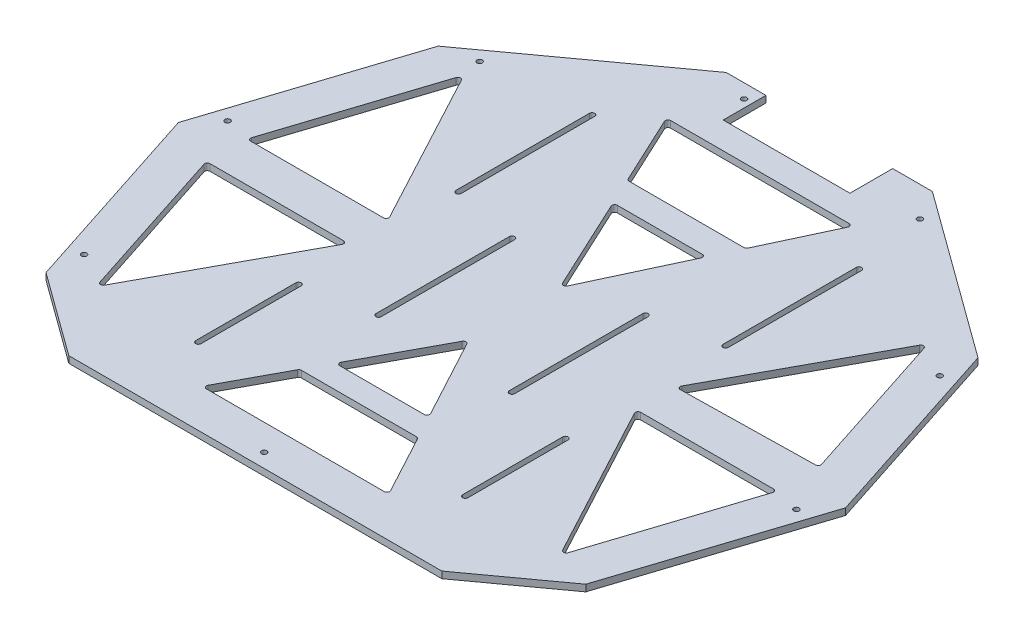
SolidWorks part; units mm, degrees
material "Alumina"
ref_plane "Front Plane" through (0, 0, 0) normal (0, 0, 1) x (1, 0, 0)
ref_plane "Top Plane" through (0, 0, 0) normal (0, 1, 0) x (1, 0, 0)
ref_plane "Right Plane" through (0, 0, 0) normal (1, 0, 0) x (0, 0, -1)
sketch "Sketch1" plane through (0, 0, 0) normal (0, 1, 0) x (1, 0, 0)
  circle A0 centre (0, 0) radius 250
extrude "Boss-Extrude1" add sketch "Sketch1" along normal blind 5
sketch "Sketch5" plane through (0, 5, 0) normal (0, 1, 0) x (1, 0, 0)
  line L0 (-139.7542, -192.3552) -> (139.7542, -192.3552)
  line L1 (202.2542, 146.9463) -> (77.2542, 237.7641)
  line L2 (77.2542, 237.7641) -> (-77.2542, 237.7641)
  line L3 (-77.2542, 237.7641) -> (-202.2542, 146.9463)
  line L4 (-202.2542, 146.9463) -> (-250, 0)
  line L5 (-250, 0) -> (-202.2542, -146.9463)
  line L7 (-202.2542, -146.9463) -> (-139.7542, -192.3552)
  line L9 (202.2542, -146.9463) -> (250, 0)
  line L10 (250, 0) -> (202.2542, 146.9463)
  line L11 (139.7542, -192.3552) -> (202.2542, -146.9463)
  line L14 (-77.2542, -237.7641) -> (77.2542, -237.7641) [skipped]
  line L15 (-202.2542, -146.9463) -> (-77.2542, -237.7641) [skipped]
  line L16 (77.2542, -237.7641) -> (202.2542, -146.9463) [skipped]
  circle A0 centre (0, 0) radius 237.7641 construction
extrude "Cut-Extrude4" cut sketch "Sketch5" against normal blind 6 flip side to cut
sketch "Sketch6" plane through (0, 0, 0) normal (0, -1, 0) x (1, 0, 0)
  circle A0 centre (-3.8992, 181.8552) radius 2
  circle A1 centre (-199.6563, 120.9633) radius 2
  circle A2 centre (-232.6258, -19.4937) radius 2
  circle A3 centre (-176.7401, -152.5047) radius 2
  circle A4 centre (-53.3458, -227.2641) radius 2
  circle A5 centre (90.4249, -215.2164) radius 2
  circle A6 centre (199.6563, -120.9633) radius 2
  circle A7 centre (232.6258, 19.4937) radius 2
extrude "Cut-Extrude5" cut sketch "Sketch6" against normal through all
sketch "Sketch7" plane through (0, 5, 0) normal (0, 1, 0) x (1, 0, 0)
  line L0 (102, 60) -> (102, 160)
  line L1 (-52, -50) -> (-52, 50)
  line L2 (-52, 50) -> (-48, 50)
  line L3 (-48, 50) -> (-48, -50)
  line L4 (-48, -50) -> (-52, -50)
  line L5 (-2, -60) -> (-2, -135)
  line L6 (48, 0) -> (48, 50)
  line L7 (48, 50) -> (52, 50)
  line L8 (52, 50) -> (52, -50)
  line L9 (52, -50) -> (48, -50)
  line L10 (48, -50) -> (48, 0)
  line L11 (98, 160) -> (98, 60)
  line L12 (-2, -135) -> (2, -135)
  line L13 (98, -60) -> (98, -135)
  line L14 (98, -135) -> (102, -135)
  line L15 (102, -60) -> (102, -135)
  line L16 (2, -60) -> (2, -135)
  line L17 (-102, -60) -> (-102, -135)
  line L18 (-102, -135) -> (-98, -135)
  line L19 (-98, -135) -> (-98, -60)
  line L20 (-102, 160) -> (-102, 60)
  line L21 (-102, 60) -> (-98, 60)
  line L22 (-98, 60) -> (-98, 160)
  line L23 (2, -135) -> (2.1286, -135.0022)
  line L24 (-2, 160) -> (-2, 60)
  line L25 (-2, 60) -> (2, 60)
  line L26 (2, 60) -> (2, 160)
  circle A0 centre (0, -60) radius 2
  circle A1 centre (100, 160) radius 2
  circle A2 centre (-50, 0) radius 2
  circle A3 centre (50, 0) radius 2
  circle A4 centre (100, 60) radius 2
  circle A5 centre (100, -60) radius 2
  circle A6 centre (100, -135) radius 2
  circle A7 centre (50, 50) radius 2
  circle A8 centre (50, -50) radius 2
  circle A9 centre (-50, -50) radius 2
  circle A10 centre (-50, 50) radius 2
  circle A11 centre (0, -135) radius 2
  circle A12 centre (-100, -60) radius 2
  circle A13 centre (-100, -135) radius 2
  circle A14 centre (-100, 60) radius 2
  circle A15 centre (-100, 160) radius 2
  circle A16 centre (0, 60) radius 2
  circle A17 centre (0, 160) radius 2
  dimension "D3" = 50
  dimension "D2" = 50
  dimension "D4" = 50
  dimension "D5" = 50
  dimension "D6" = 50
  dimension "D7" = 50
  dimension "D8" = 10
  dimension "D9" = 100
  dimension "D10" = 10
  dimension "D11" = 75
extrude "Cut-Extrude6" cut sketch "Sketch7" against normal through all contours A15 L20 A14 L22 | L21 A14 | L21 A14 | A15 | A4 | A4 L0 A1 L11 | A1 | A6 L15 A5 L13 | L14 A6 | L14 A6 | A13 L19 A12 L17 | L18 A13 | L18 A13 | A9 L3 A2 L1 | L4 A9 | A10 L1 A2 L3 | A8 L8 A3 L10 | A7 L6 A3 L8 | L9 A8 | L9 A8 | L7 A7 | L7 A7 | A2 | A3
sketch "Sketch8" plane through (0, 0, 0) normal (0, -1, 0) x (1, 0, 0)
  line L0 (77.2542, -237.7641) -> (-77.2542, -237.7641) construction
  line L1 (47.4958, -237.7641) -> (-47.4942, -237.7641)
  line L2 (47.4958, -205.7641) -> (47.4958, -237.7641)
  line L3 (47.4958, -205.7641) -> (-47.4942, -205.7641)
  line L4 (-47.4942, -237.7641) -> (-47.4942, -205.7641)
  dimension "D1" = 29.76
extrude "Cut-Extrude7" cut sketch "Sketch8" against normal through all
sketch "Sketch9" plane through (0, 5, 0) normal (0, 1, 0) x (1, 0, 0)
  line L0 (0, 35.7641) -> (-70, 185.7641)
  line L1 (-70, 185.7641) -> (70, 185.7641)
  line L2 (70, 185.7641) -> (0, 35.7641)
  line L3 (47.4958, 205.7641) -> (-47.4942, 205.7641) construction
  line L4 (-44.3333, 130.7641) -> (44.3333, 130.7641)
  line L5 (-35, 110.7641) -> (35, 110.7641)
  line L6 (-218.7416, -0.8784) -> (-173.7026, 137.7371)
  line L7 (-202.2542, 146.9463) -> (-250, 0) construction
  line L8 (100, 0) -> (173.7026, -137.7371)
  line L9 (-218.7416, -0.8784) -> (-174.3945, -137.3646)
  line L10 (-250, 0) -> (-202.2542, -146.9463) construction
  line L11 (-100, 0) -> (-173.7026, 137.7371)
  line L12 (-100, 0) -> (-174.3945, -137.3646)
  line L13 (-70, -162.3552) -> (70, -162.3552)
  line L14 (218.7416, 0.8784) -> (173.7026, -137.7371)
  line L15 (218.7416, 0.8784) -> (174.3945, 137.3646)
  line L16 (100, 0) -> (174.3945, 137.3646)
  line L17 (-139.7542, -192.3552) -> (139.7542, -192.3552) construction
  line L18 (-70, -162.3552) -> (0, -32.3552)
  line L19 (0, -32.3552) -> (70, -162.3552)
  line L20 (-35, -97.3552) -> (35, -97.3552)
  line L21 (-44.3333, -114.6886) -> (44.3333, -114.6886)
  line L22 (-108.0264, 15) -> (-213.5823, 15)
  line L23 (-108.0264, -14.8203) -> (-214.2116, -14.8203)
  line L24 (107.9303, -14.8203) -> (213.6407, -14.8203)
  line L25 (213.6407, 16.5772) -> (107.9303, 14.6428)
  dimension "D1" = 20
  dimension "D2" = 20
  dimension "D3" = 30
  dimension "D4" = 30
  dimension "D5" = 130
  dimension "D6" = 15
extrude "Cut-Extrude8" cut sketch "Sketch9" against normal through all contours L12 L23 L9 | L22 L11 L6 | L0 L4 L2 L1 | L5 L0 L2 | L18 L20 L19 | L21 L18 L13 L19 | L24 L8 L14 | L25 L15 L16
fillet "Fillet1" radius 2 26 edges at (107.9303, 2.5, -14.6428) (107.9303, 2.5, 14.8203) (70, 2.5, 162.3552) (35, 2.5, 97.3552) (213.6407, 2.5, 14.8203) (-108.0264, 2.5, 14.8203) (-44.3333, 2.5, 114.6886) (44.3333, 2.5, 114.6886) (0, 2.5, 32.3552) (-214.2116, 2.5, 14.8203) (-35, 2.5, 97.3552) (-70, 2.5, 162.3552) (-174.3945, 2.5, 137.3646) (173.7026, 2.5, 137.7371) (44.3333, 2.5, -130.7641) (-44.3333, 2.5, -130.7641) (0, 2.5, -35.7641) (213.6407, 2.5, -16.5772) (-108.0264, 2.5, -15) (-213.5823, 2.5, -15) (-173.7026, 2.5, -137.7371) (-35, 2.5, -110.7641) (174.3945, 2.5, -137.3646) (35, 2.5, -110.7641) (70, 2.5, -185.7641) (-70, 2.5, -185.7641)
